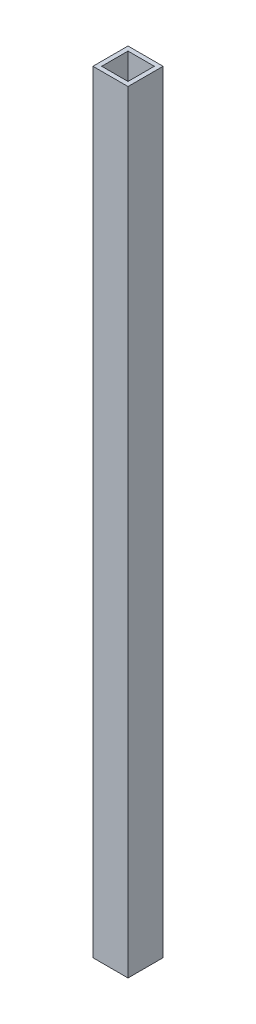
SolidWorks part; units mm, degrees
ref_plane "Front Plane" through (0, 0, 0) normal (0, 0, 1) x (1, 0, 0)
ref_plane "Top Plane" through (0, 0, 0) normal (0, 1, 0) x (1, 0, 0)
ref_plane "Right Plane" through (0, 0, 0) normal (1, 0, 0) x (0, 0, -1)
sketch "Sketch1" plane through (0, 0, 0) normal (0, 1, 0) x (1, 0, 0)
  line L0 (-9.525, 9.525) -> (9.525, 9.525)
  line L1 (-12.7, 12.7) -> (12.7, 12.7)
  line L2 (-12.7, 12.7) -> (-12.7, -12.7)
  line L3 (-12.7, -12.7) -> (12.7, -12.7)
  line L4 (12.7, 12.7) -> (12.7, -12.7)
  line L5 (9.525, 9.525) -> (9.525, -9.525)
  line L6 (-9.525, -9.525) -> (9.525, -9.525)
  line L7 (-9.525, 9.525) -> (-9.525, -9.525)
  point P7 (-11.5879, -4.4095)
  point P8 (13.8121, -1.4698)
  dimension "D1" = 25.4
  dimension "D2" = 25.4
  dimension "D3" = 12.7
  dimension "D4" = 12.7
  dimension "D5" = 3.175
extrude "Boss-Extrude1" add sketch "Sketch1" along normal blind 558.8
